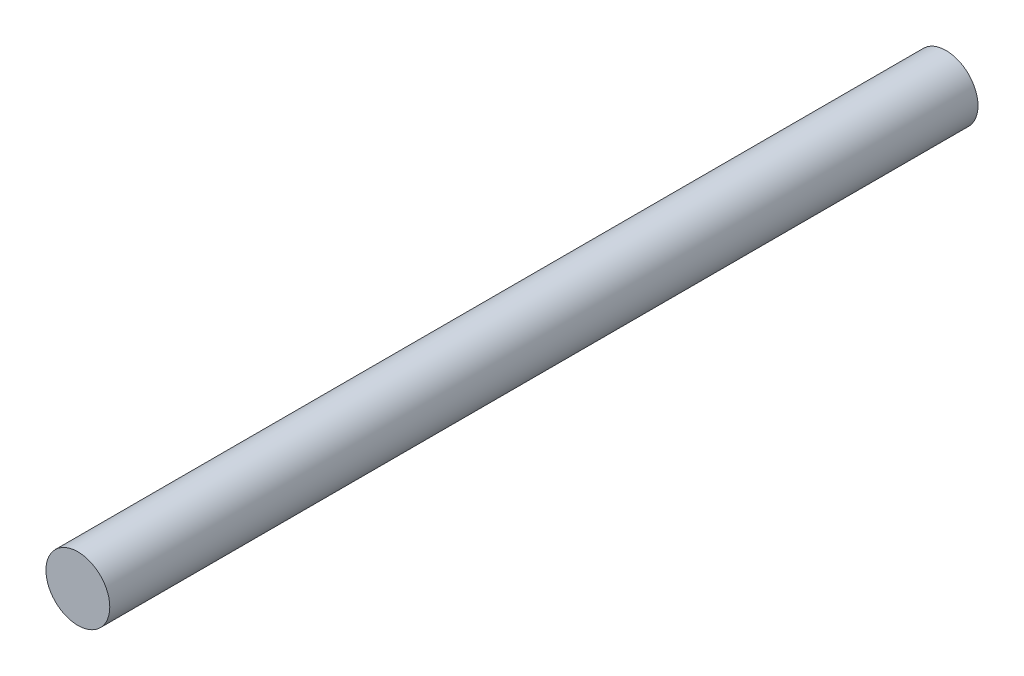
SolidWorks part; units mm, degrees
material "Plain Carbon Steel"
ref_plane "Front Plane" through (0, 0, 0) normal (0, 0, 1) x (1, 0, 0)
ref_plane "Top Plane" through (0, 0, 0) normal (0, 1, 0) x (1, 0, 0)
ref_plane "Right Plane" through (0, 0, 0) normal (1, 0, 0) x (0, 0, -1)
sketch "Sketch1" plane through (0, 0, 0) normal (0, 0, 1) x (1, 0, 0)
  circle A0 centre (0, 0) radius 1.5875
  dimension "D1" = 3.175
extrude "Body" add sketch "Sketch1" against normal blind 43.18
sketch "Sketch2" plane through (0, 0, 0) normal (0, 1, 0) x (1, 0, 0)
  line L0 (0, 21.59) -> (-8.5875, 21.59) construction
  line L1 (-2.2429, 19.05) -> (-2.2429, 20.32)
  line L2 (-2.2429, 20.32) -> (-1.3335, 19.795)
  line L3 (-2.2429, 22.86) -> (-1.3335, 23.385)
  line L4 (-1.3335, 19.575) -> (-2.2429, 19.05)
  line L5 (-1.3335, 23.605) -> (-2.2429, 24.13)
  line L6 (-2.2429, 24.13) -> (-2.2429, 22.86)
  line L9 (0, 0) -> (0, 43.18) construction
  line L10 (1.5875, 43.18) -> (-1.5875, 43.18) construction
  line L11 (1.5875, 43.18) -> (-1.5875, 43.18) construction
  arc A0 (-1.3335, 19.575) -> (-1.3335, 19.795) centre (-1.397, 19.685) ccw
  arc A1 (-1.3335, 23.605) -> (-1.3335, 23.385) centre (-1.397, 23.495) cw
  point P15 (0, 21.59)
  dimension "D4" = 0.254
  dimension "D3" = 1.27
  dimension "D1" = 60
  dimension "D2" = 60
  dimension "D5" = 1.397
  dimension "D6" = 1.905
revolve "WireSlots" [suppressed] cut sketch "Sketch2" angle 360 about L9
